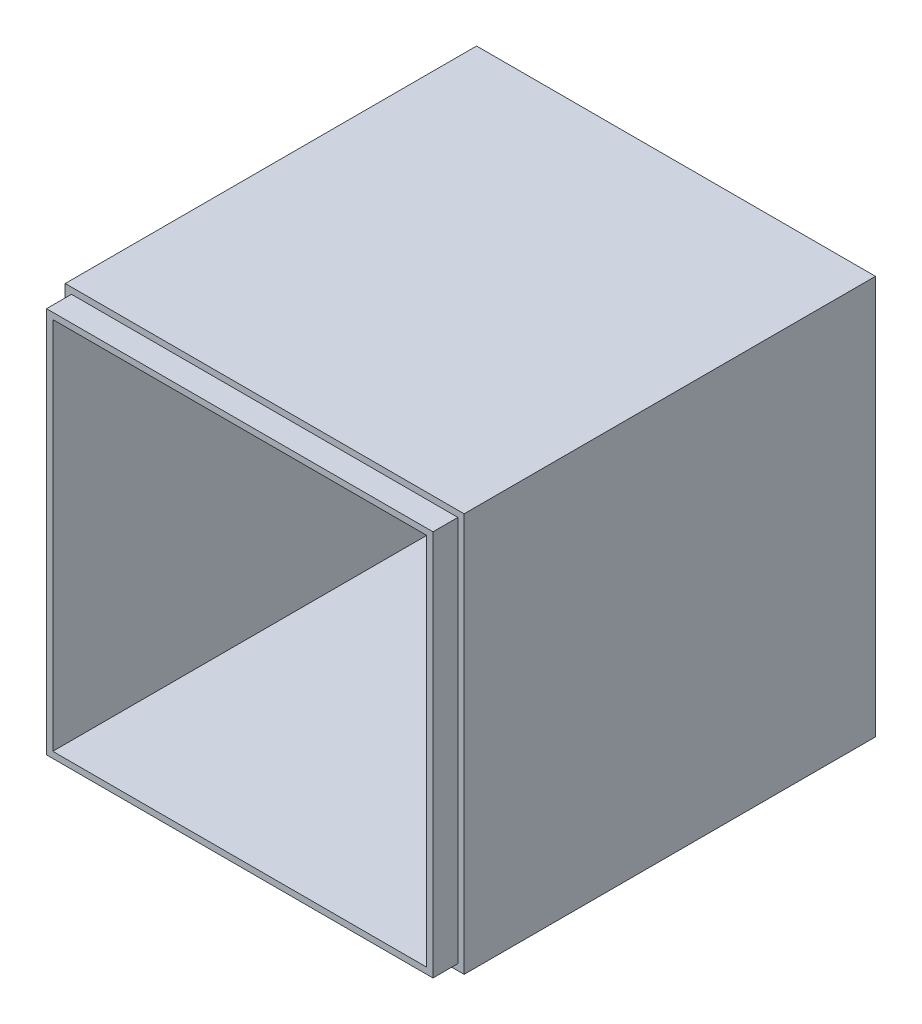
SolidWorks part; units mm, degrees
material "Custom Plastic"
ref_plane "X-Y Datum" through (0, 0, 0) normal (0, 0, 1) x (1, 0, 0)
ref_plane "X-Z Datum" through (0, 0, 0) normal (0, 1, 0) x (1, 0, 0)
ref_plane "Y-Z Datum" through (0, 0, 0) normal (1, 0, 0) x (0, 0, -1)
sketch "Sketch1" plane through (0, 0, 0) normal (0, 0, 1) x (1, 0, 0)
  line L1 (-40.64, 40.64) -> (40.64, 40.64)
  line L2 (-40.64, 40.64) -> (-40.64, -40.64)
  line L3 (-40.64, -40.64) -> (40.64, -40.64)
  line L4 (40.64, 40.64) -> (40.64, -40.64)
  line L5 (-40.64, 40.64) -> (40.64, -40.64) construction
  line L6 (-40.64, -40.64) -> (40.64, 40.64) construction
  point P0 (0, 0)
  dimension "D1" = 81.28
  dimension "D2" = 81.28
extrude "Boss-Extrude1" add sketch "Sketch1" along normal blind 88.9
shell "Shell1" thickness 2.54
sketch "Sketch2" plane through (0, 0, 88.9) normal (0, 0, 1) x (1, 0, 0)
  line L12 (-45.8908, 43.4759) -> (45.8908, 43.4759)
  line L13 (-45.8908, 43.4759) -> (-45.8908, -43.4759)
  line L14 (-45.8908, -43.4759) -> (45.8908, -43.4759)
  line L15 (39.37, -39.37) -> (39.37, 39.37)
  line L16 (-39.37, 39.37) -> (-39.37, -39.37)
  line L17 (39.37, 39.37) -> (-39.37, 39.37)
  line L18 (-39.37, -39.37) -> (39.37, -39.37)
  line L19 (39.37, -39.37) -> (39.37, 39.37)
  line L20 (-39.37, 39.37) -> (-39.37, -39.37)
  line L21 (39.37, 39.37) -> (-39.37, 39.37)
  line L22 (-39.37, -39.37) -> (39.37, -39.37)
  line L23 (45.8908, 43.4759) -> (45.8908, -43.4759)
  line L24 (-45.8908, 43.4759) -> (45.8908, -43.4759) construction
  line L25 (-45.8908, -43.4759) -> (45.8908, 43.4759) construction
  point P0 (0, 0)
  dimension "D1" = 1.27
extrude "Cut-Extrude1" cut sketch "Sketch2" against normal blind 5.08
